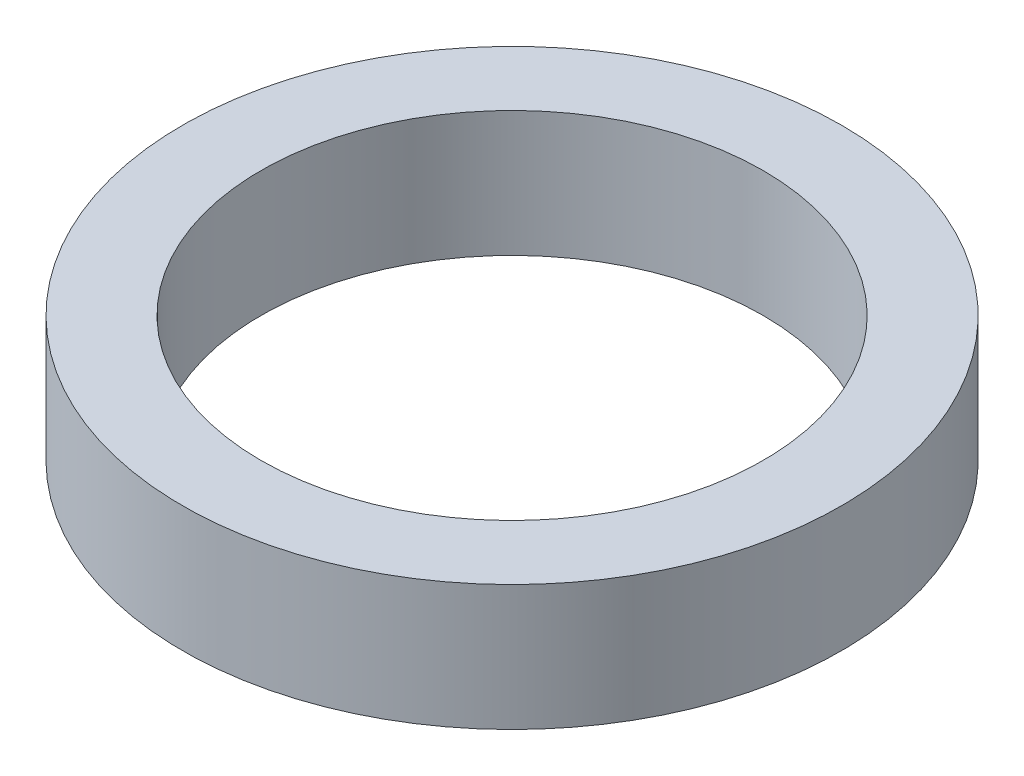
SolidWorks part; units mm, degrees
ref_plane "Front Plane" through (0, 0, 0) normal (0, 0, 1) x (1, 0, 0)
ref_plane "Top Plane" through (0, 0, 0) normal (0, 1, 0) x (1, 0, 0)
ref_plane "Right Plane" through (0, 0, 0) normal (1, 0, 0) x (0, 0, -1)
sketch "Reconstructed nominal axial profile" plane through (0, 0, 0) normal (0, 0, 1) x (1, 0, 0)
  line L0 (0, -500) -> (0, 50) construction
  line L1 (4, -13) -> (4, -11)
  line L2 (4, -11) -> (5.25, -11)
  line L3 (5.25, -11) -> (5.25, -13)
  line L4 (5.25, -13) -> (4, -13)
revolve "Native revolved geometry" add sketch "Reconstructed nominal axial profile" angle 360 about L0
